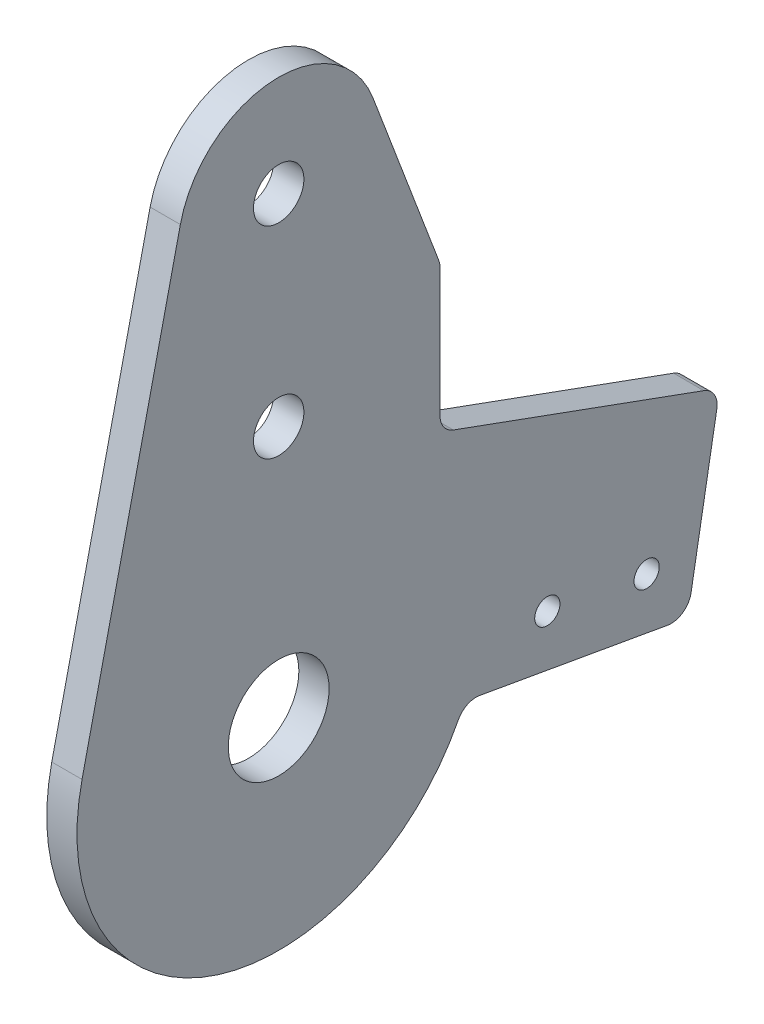
SolidWorks part; units mm, degrees
ref_plane "Front Plane" through (0, 0, 0) normal (0, 0, 1) x (1, 0, 0)
ref_plane "Top Plane" through (0, 0, 0) normal (0, 1, 0) x (1, 0, 0)
ref_plane "Right Plane" through (0, 0, 0) normal (1, 0, 0) x (0, 0, -1)
sketch "Sketch1" plane through (0, 0, 0) normal (1, 0, 0) x (0, 0, -1)
  line L5 (-50, 15) -> (-50, -5) construction
  line L7 (-59.75, 17.2222) -> (-69.4999, -25.5556)
  line L21 (-20, -43.9) -> (-18.4372, -35.0367) construction
  line L25 (-29.8481, -42.1635) -> (-10.1519, -45.6365) construction
  line L31 (-34, 1) -> (-40.649, 18.544)
  line L34 (-34, -13.4758) -> (-34, 1)
  line L36 (-30, -5) -> (-10, -5) construction
  line L37 (-10, -5) -> (-10, 0) construction
  line L38 (-10, 0) -> (-30, 0) construction
  line L39 (-30, 0) -> (-30, -5) construction
  line L40 (-20.9455, -8.6496) -> (-22.6556, -13.3481) construction
  line L41 (-22.6556, -13.3481) -> (-3.8618, -20.1885) construction
  line L42 (-3.8618, -20.1885) -> (-2.1517, -15.49) construction
  line L43 (-2.1517, -15.49) -> (-20.9455, -8.6496) construction
  line L44 (-30, -5) -> (-50, -30) construction
  line L45 (-50, -30) -> (-22.6556, -13.3481) construction
  line L47 (-9.4573, -41.6973) -> (-6.2613, -23.5718)
  line L48 (-34, -13.4758) -> (-6.2613, -23.5718)
  line L49 (-8.8181, -38.0718) -> (-67.4858, -16.7185) construction
  line L51 (-13.2587, -16.7683) -> (-19.5861, -34.1526) construction
  line L54 (-23.3612, -34.1685) -> (-13.5131, -35.905) construction
  line L55 (-9.4573, -41.6973) -> (-31.582, -37.7961)
  circle A0 centre (-50, -30) radius 5
  circle A2 centre (-50, 15) radius 2.5
  arc A8 (-40.649, 18.544) -> (-59.75, 17.2222) centre (-50, 15) ccw
  arc A11 (-69.4999, -25.5556) -> (-31.582, -37.7961) centre (-50, -30) ccw
  circle A12 centre (-50, -5) radius 2.5
  circle A18 centre (-23.3612, -34.1685) radius 1.25
  circle A19 centre (-13.5131, -35.905) radius 1.25
  point P14 (-20, -43.9)
  point P17 (-20, -5)
  point P20 (-18.4372, -35.0367)
  point P37 (-20, -5)
  dimension "D3" = 5
  dimension "D7" = 10
  dimension "D8" = 7.5
  dimension "D6" = 20
  dimension "D25" = 2.5
  dimension "D11" = 5
  dimension "D4" = 50
  dimension "D5" = 30
  dimension "D9" = 25
  dimension "D10" = 5
  dimension "D12" = 10
  dimension "D13" = 20
  dimension "D14" = 38.9
  dimension "D15" = 9
  dimension "D16" = 10
  dimension "D17" = 4
  dimension "D18" = 6
  dimension "D19" = 20
  dimension "D20" = 20
  dimension "D21" = 4
  dimension "D22" = 20
  dimension "D23" = 20
  dimension "D24" = 14.5
extrude "Boss-Extrude1" add sketch "Sketch1" along normal blind 3
fillet "Fillet1" radius 2 5 edges at (1.5, 1, 34) (1.5, -23.5718, 6.2613) (1.5, -13.4758, 34) (1.5, -37.7961, 31.582) (1.5, -41.6973, 9.4573)
